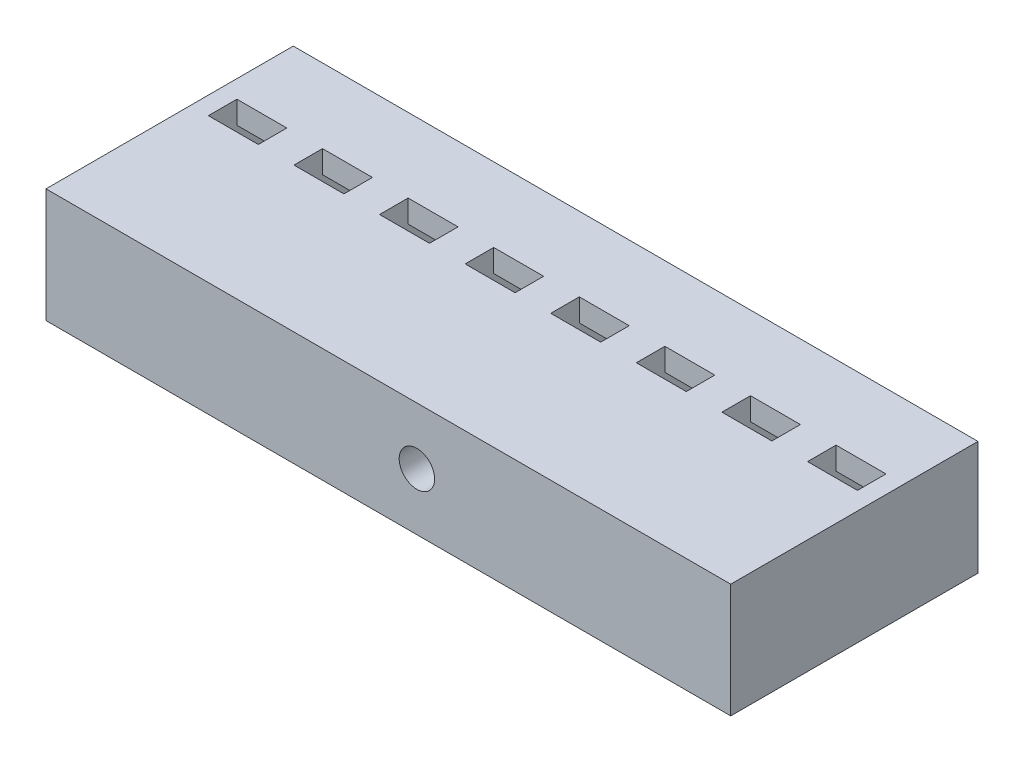
SolidWorks part; units mm, degrees
ref_plane "Front Plane" through (0, 0, 0) normal (0, 0, 1) x (1, 0, 0)
ref_plane "Top Plane" through (0, 0, 0) normal (0, 1, 0) x (1, 0, 0)
ref_plane "Right Plane" through (0, 0, 0) normal (1, 0, 0) x (0, 0, -1)
sketch "Sketch1" plane through (0, 0, 0) normal (0, 1, 0) x (1, 0, 0)
  line L1 (0, 0) -> (-72, 0)
  line L2 (0, 0) -> (0, 22)
  line L3 (0, 22) -> (-72, 22)
  line L4 (-72, 0) -> (-72, 22)
  line L5 (0, 0) -> (-72, 22) construction
  line L6 (0, 22) -> (-72, 0) construction
  point P4 (-36, 11)
  dimension "D1" = 22
  dimension "D2" = 72
extrude "Boss-Extrude1" add sketch "Sketch1" along normal blind 12
sketch "Sketch2" plane through (0, 12, 0) normal (0, 1, 0) x (1, 0, 0)
  line L0 (-72, 0) -> (-63, 0) construction
  line L2 (-72, 0) -> (0, 0) construction
  line L7 (-67.5, 0) -> (-67.5, 12.7) construction
  line L13 (-70.125, 14.2) -> (-64.875, 14.2)
  line L19 (-70.125, 14.2) -> (-70.125, 11.2)
  line L20 (-70.125, 11.2) -> (-64.875, 11.2)
  line L21 (-64.875, 14.2) -> (-64.875, 11.2)
  line L22 (-70.125, 14.2) -> (-64.875, 11.2) construction
  line L23 (-70.125, 11.2) -> (-64.875, 14.2) construction
  point P7 (-36, 23.9)
  point P23 (-73.5, 12.7)
  dimension "D1" = 9
  dimension "D2" = 5.25
  dimension "D3" = 3
extrude "Cut-Extrude1" cut sketch "Sketch2" against normal through all
pattern_linear "LPattern2" count 8 spacing 9 along (1, 0, 0) of "Cut-Extrude1"
sketch "Sketch3" plane through (0, 0, -22) normal (0, 0, -1) x (-1, 0, 0)
  line L0 (72, 6) -> (63, 6) construction
  line L2 (72, 12) -> (72, 0) construction
  line L8 (64.875, 2.375) -> (70.125, 2.375)
  line L9 (64.875, 2.375) -> (64.875, 9.625)
  line L10 (64.875, 9.625) -> (70.125, 9.625)
  line L11 (70.125, 2.375) -> (70.125, 9.625)
  line L12 (64.875, 2.375) -> (70.125, 9.625) construction
  line L13 (64.875, 9.625) -> (70.125, 2.375) construction
  point P4 (64.5, 6)
  point P5 (67.5, 6)
  dimension "D1" = 9
  dimension "D2" = 7.25
  dimension "D3" = 5.25
extrude "Cut-Extrude2" cut sketch "Sketch3" against normal through all
pattern_linear "LPattern3" count 8 spacing 9 along (1, 0, 0) of "Cut-Extrude2"
sketch "Sketch4" plane through (0, 0, 0) normal (0, 0, 1) x (1, 0, 0)
  line L1 (-72, 0) -> (0, 0)
  line L2 (-72, 0) -> (-72, 12)
  line L3 (-72, 12) -> (0, 12)
  line L4 (0, 0) -> (0, 12)
  line L5 (-72, 0) -> (0, 12) construction
  line L6 (-72, 12) -> (0, 0) construction
  point P4 (-36, 6)
extrude "Boss-Extrude2" add sketch "Sketch4" against normal blind 4
sketch "Sketch11" plane through (0, 0, 0) normal (0, 0, 1) x (1, 0, 0)
  line L1 (-72, 12) -> (0, 12)
  line L2 (-72, 12) -> (-72, 0)
  line L3 (-72, 0) -> (0, 0)
  line L4 (0, 12) -> (0, 0)
extrude "Boss-Extrude3" add sketch "Sketch11" along normal blind 4
sketch "Sketch12" plane through (0, 0, 4) normal (0, 0, 1) x (1, 0, 0)
  line L0 (0, 6) -> (-33, 6) construction
  line L1 (0, 0) -> (0, 12) construction
  circle A0 centre (-33, 6) radius 1.865
  dimension "D2" = 3.73
  dimension "D1" = 33
extrude "Cut-Extrude9" cut sketch "Sketch12" against normal blind 6
